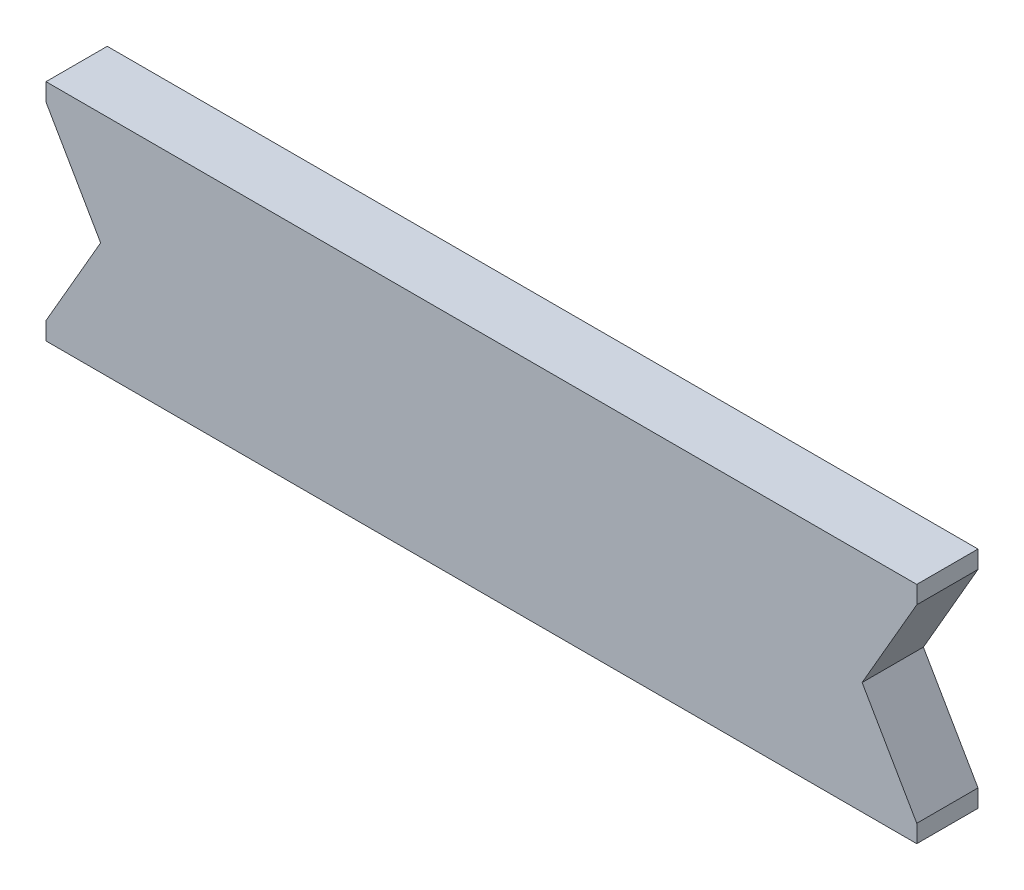
SolidWorks part; units mm, degrees
ref_plane "Front Plane" through (0, 0, 0) normal (0, 0, 1) x (1, 0, 0)
ref_plane "Top Plane" through (0, 0, 0) normal (0, 1, 0) x (1, 0, 0)
ref_plane "Right Plane" through (0, 0, 0) normal (1, 0, 0) x (0, 0, -1)
sketch "Sketch1" plane through (0, 0, 0) normal (0, 0, 1) x (1, 0, 0)
  line L0 (55, 0) -> (-55, 0) construction
  line L1 (-9.3246, 0) -> (-10.9123, 2.75)
  line L2 (-10.9123, 2.75) -> (-14.0877, 2.75)
  line L3 (-14.0877, 2.75) -> (-15.6754, 0)
  line L4 (-15.6754, 0) -> (-14.0877, -2.75)
  line L5 (-14.0877, -2.75) -> (-10.9123, -2.75)
  line L6 (-10.9123, -2.75) -> (-9.3246, 0)
  line L7 (0, 0) -> (0, 18.6571) construction
  line L8 (0, -54.6431) -> (0, 54.6431) construction
  line L9 (10.9123, -2.75) -> (9.3246, 0)
  line L10 (14.0877, -2.75) -> (10.9123, -2.75)
  line L11 (15.6754, 0) -> (14.0877, -2.75)
  line L12 (14.0877, 2.75) -> (15.6754, 0)
  line L13 (10.9123, 2.75) -> (14.0877, 2.75)
  line L14 (9.3246, 0) -> (10.9123, 2.75)
  circle A0 centre (-12.5, 0) radius 2.75 construction
  circle A1 centre (12.5, 0) radius 2.75 construction
  dimension "D1" = 5.5
  dimension "D2" = 25
sketch "Sketch2" plane through (0, 0, 0) normal (0, 0, 1) x (1, 0, 0)
  line L0 (-10.9123, 2.75) -> (-9.3246, 0)
  line L1 (-9.3246, 0) -> (-10.9123, -2.75)
  line L2 (-10.9123, -2.75) -> (10.9123, -2.75)
  line L3 (10.9123, -2.75) -> (9.3246, 0)
  line L4 (9.3246, 0) -> (10.9123, 2.75)
  line L5 (10.9123, 2.75) -> (-10.9123, 2.75)
extrude "Boss-Extrude1" add sketch "Sketch2" along normal blind 1.5
sketch "Sketch3" plane through (0, 0, 1.5) normal (0, 0, 1) x (1, 0, 0)
  line L0 (-10.9123, -2.75) -> (10.9123, -2.75) construction
  line L1 (10.9123, 2.75) -> (10.6623, 2.75)
  line L2 (10.9123, 2.75) -> (10.9123, -2.75)
  line L3 (10.9123, -2.75) -> (10.6623, -2.75)
  line L4 (10.6623, 2.75) -> (10.6623, -2.75)
  line L6 (-10.9123, 2.75) -> (-10.6623, 2.75)
  line L7 (-10.9123, 2.75) -> (-10.9123, -2.75)
  line L8 (-10.9123, -2.75) -> (-10.6623, -2.75)
  line L9 (-10.6623, 2.75) -> (-10.6623, -2.75)
  dimension "D1" = 0.25
extrude "Cut-Extrude1" cut sketch "Sketch3" against normal through all
